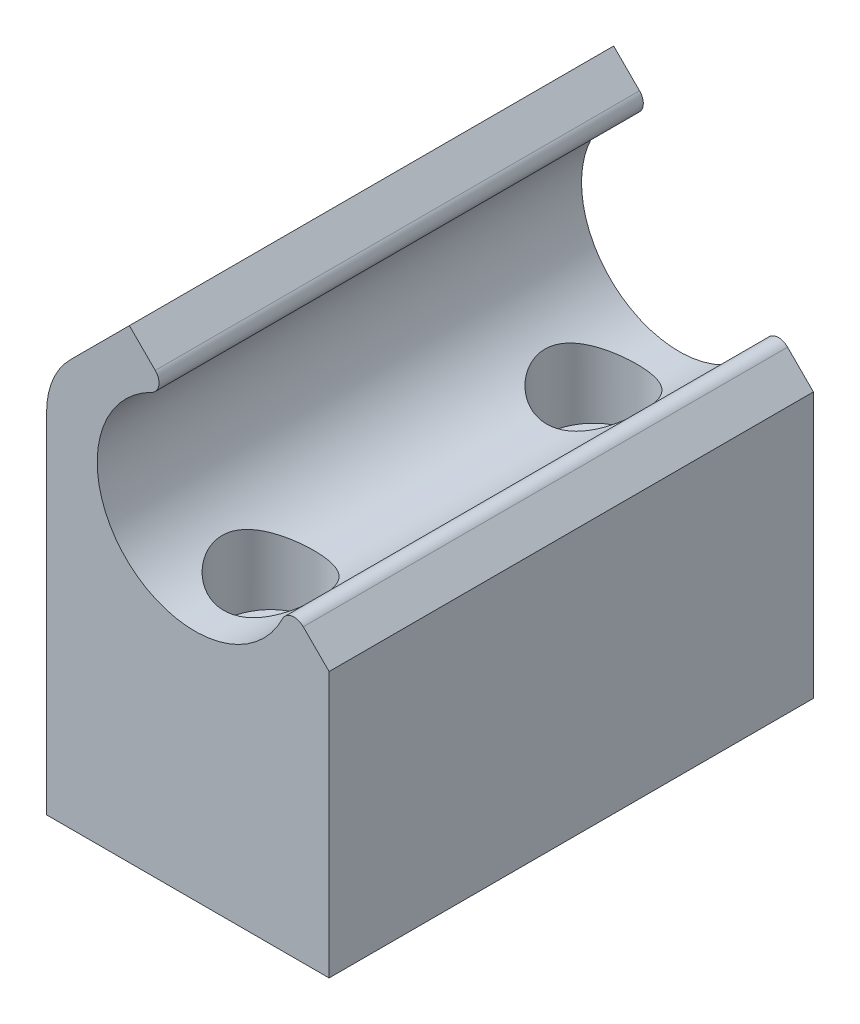
SolidWorks part; units mm, degrees
ref_plane "Front Plane" through (0, 0, 0) normal (0, 0, 1) x (1, 0, 0)
ref_plane "Top Plane" through (0, 0, 0) normal (0, 1, 0) x (1, 0, 0)
ref_plane "Right Plane" through (0, 0, 0) normal (1, 0, 0) x (0, 0, -1)
sketch "Sketch1" plane through (0, 0, 0) normal (0, 0, 1) x (1, 0, 0)
  line L0 (0, 0) -> (17.5, 0)
  line L1 (17.5, 0) -> (17.5, 16.44)
  line L2 (17.5, 16.44) -> (15.0251, 18.9149)
  line L3 (7.6032, 26.3368) -> (5.1283, 28.8117)
  line L4 (5.1283, 28.8117) -> (0, 23.6833)
  line L5 (0, 23.6833) -> (0, 0)
  arc A0 (15.0251, 18.9149) -> (7.6032, 26.3368) centre (9.1858, 20.4974) cw
  dimension "D1" = 6.05
  dimension "D2" = 3.5
  dimension "D3" = 17.5
  dimension "D4" = 16.44
  dimension "D5" = 3.01
  dimension "D6" = 45
extrude "Boss-Extrude1" add sketch "Sketch1" along normal blind 30
fillet "Fillet1" radius 0.8 2 edges at (15.0251, 18.9149, 15) (7.6032, 26.3368, 15)
ref_plane "Plane1" through (0, 17.8284, 0) normal (0, -1, 0) x (-1, 0, 0)
sketch "Sketch3" plane through (0, 17.8284, 0) normal (0, -1, 0) x (-1, 0, 0)
  line L0 (-3.1358, 0) -> (-14.6152, 0) construction
  line L1 (-3.1358, 0) -> (-14.6152, 0) construction
  circle A0 centre (-8.8755, -5) radius 3
  circle A1 centre (-8.8755, -25) radius 3
  point P7 (-8.8755, 0)
  dimension "D1" = 6
  dimension "D2" = 5
  dimension "D3" = 20
extrude "Cut-Extrude1" cut sketch "Sketch3" along normal blind 7
sketch "Sketch4" plane through (0, 17.8284, 0) normal (0, -1, 0) x (-1, 0, 0)
  circle A0 centre (-8.8755, -5) radius 1.55
  circle A1 centre (-8.8755, -25) radius 1.55
  dimension "D1" = 3.1
  dimension "D2" = 3.1
extrude "Cut-Extrude2" cut sketch "Sketch4" along normal through all
fillet "Fillet2" radius 5 1 edges at (0, 23.6833, 15)
